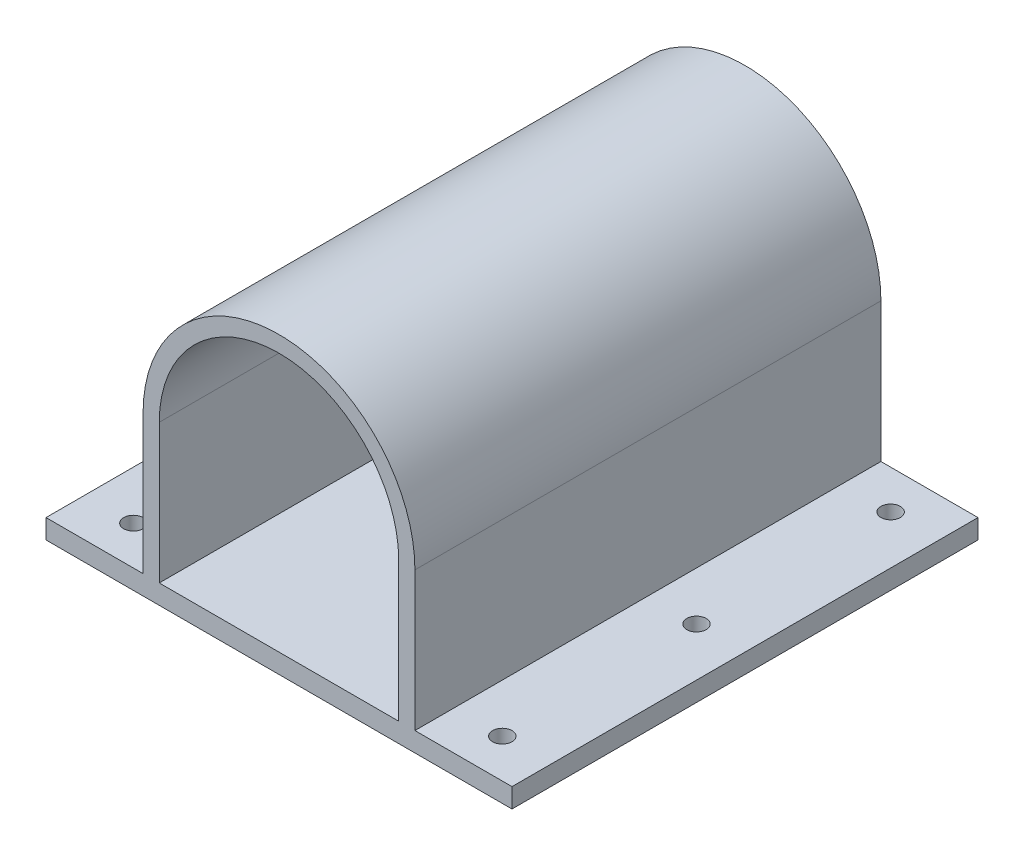
SolidWorks part; units mm, degrees
ref_plane "Front Plane" through (0, 0, 0) normal (0, 0, 1) x (1, 0, 0)
ref_plane "Top Plane" through (0, 0, 0) normal (0, 1, 0) x (1, 0, 0)
ref_plane "Right Plane" through (0, 0, 0) normal (1, 0, 0) x (0, 0, -1)
sketch "Sketch1" plane through (0, 0, 0) normal (0, 0, 1) x (1, 0, 0)
  line L0 (-21, 0) -> (-21, -21.5)
  line L1 (-21, -21.5) -> (-36, -21.5)
  line L2 (-36, -21.5) -> (-36, -24.5)
  line L3 (-36, -24.5) -> (36, -24.5)
  line L4 (36, -24.5) -> (36, -21.5)
  line L5 (36, -21.5) -> (21, -21.5)
  line L6 (21, -21.5) -> (21, 0)
  line L7 (0, 0) -> (-7, 0) construction
  line L8 (0, 0) -> (0, -15.5) construction
  line L9 (-21, -21.5) -> (21, -21.5) construction
  arc A0 (21, 0) -> (-21, 0) centre (0, 0) ccw
  circle A2 centre (0, -15.5) radius 1.65
  circle A3 centre (-13.4234, -7.75) radius 1.65
  circle A4 centre (-13.4234, 7.75) radius 1.65
  circle A5 centre (0, 15.5) radius 1.65
  circle A6 centre (13.4234, 7.75) radius 1.65
  circle A7 centre (13.4234, -7.75) radius 1.65
  circle A8 centre (0, 0) radius 18.5 construction
  circle A9 centre (-7, 0) radius 6.15
  point P15 (0, -18.5)
  point P27 (0, 0)
  dimension "D1" = 42
  dimension "D6" = 3
  dimension "D7" = 3.3
  dimension "D10" = 37
  dimension "D11" = 2.5
  dimension "D12" = 90
  dimension "D3" = 12.3
  dimension "D2" = 7
  dimension "D4" = 72
  dimension "D5" = 3
  dimension "D8" = 15.5
  dimension "D9" = 6
extrude "Boss-Extrude1" add sketch "Sketch1" along normal blind 72
sketch "Sketch2" plane through (0, 0, 72) normal (0, 0, 1) x (1, 0, 0)
  line L0 (-18.5, 0) -> (-18.5, -21.5)
  line L2 (-18.5, -21.5) -> (18.5, -21.5)
  line L3 (18.5, -21.5) -> (18.5, 0)
  line L4 (-21, -21.5) -> (-36, -21.5) construction
  arc A0 (18.5, 0) -> (-18.5, 0) centre (0, 0) ccw
  arc A1 (-18.5, 0) -> (18.5, 0) centre (0, 0) ccw construction
  dimension "D1" = 37
extrude "Cut-Extrude1" cut sketch "Sketch2" against normal blind 57
sketch "Sketch3" plane through (0, -21.5, 0) normal (0, 1, 0) x (1, 0, 0)
  line L0 (0, 0) -> (0, -72) construction
  line L1 (-21, -72) -> (21, -72) construction
  line L2 (-28.5, 0) -> (-28.5, -72) construction
  line L3 (-21, 0) -> (-36, 0) construction
  line L4 (-21, -72) -> (-36, -72) construction
  circle A0 centre (-28.5, -36) radius 1.5
  circle A1 centre (-28.5, -6) radius 1.5
  circle A2 centre (-28.5, -66) radius 1.5
  circle A3 centre (28.5, -66) radius 1.5
  circle A4 centre (28.5, -6) radius 1.5
  circle A5 centre (28.5, -36) radius 1.5
  dimension "D1" = 30
  dimension "D2" = 30
  dimension "D3" = 3
extrude "Cut-Extrude2" cut sketch "Sketch3" against normal through all
fillet "Fillet1" radius 6 1 edges at (-36, -23, 0)
